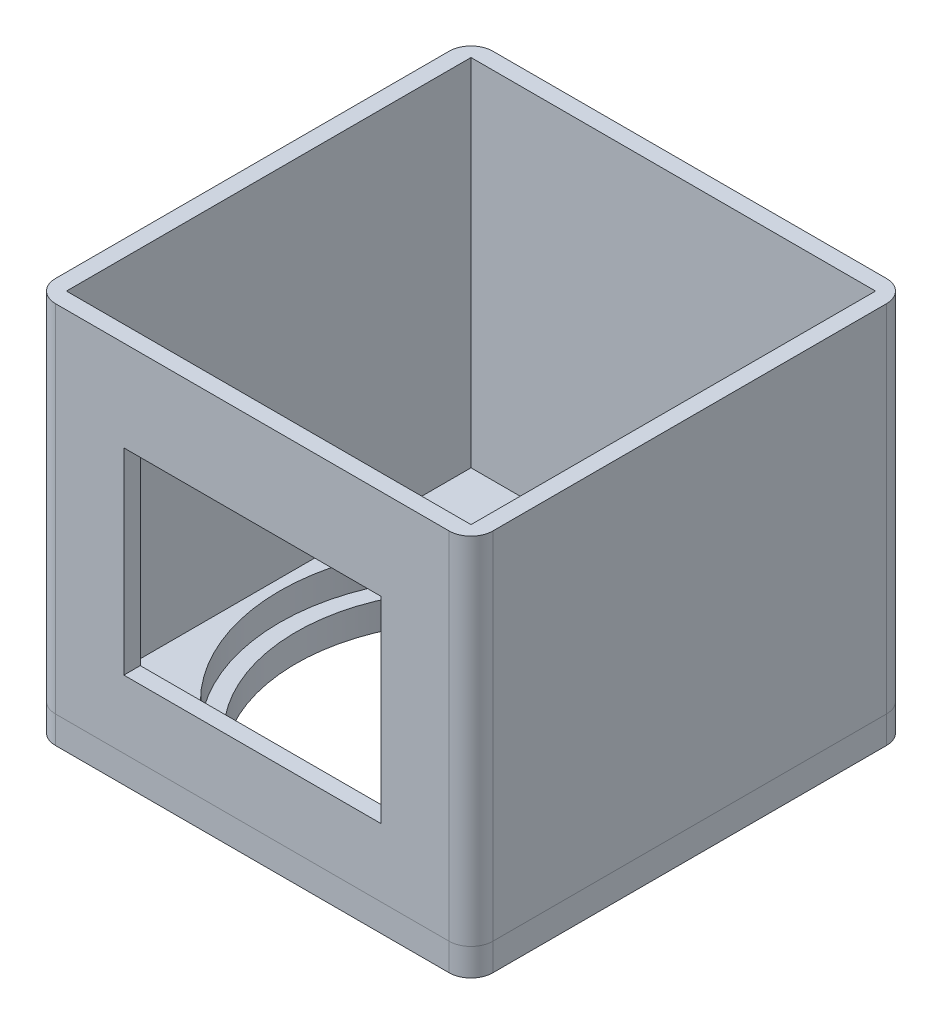
SolidWorks part; units mm, degrees
ref_plane "Front Plane" through (0, 0, 0) normal (0, 0, 1) x (1, 0, 0)
ref_plane "Top Plane" through (0, 0, 0) normal (0, 1, 0) x (1, 0, 0)
ref_plane "Right Plane" through (0, 0, 0) normal (1, 0, 0) x (0, 0, -1)
sketch "Sketch1" plane through (0, 0, 0) normal (0, 1, 0) x (1, 0, 0)
  circle A0 centre (0, 0) radius 35
  circle A1 centre (0, 0) radius 32
  dimension "D1" = 70
  dimension "D2" = 64
extrude "Boss-Extrude1" add sketch "Sketch1" along normal blind 5
sketch "Sketch2" plane through (0, 5, 0) normal (0, 1, 0) x (1, 0, 0)
  line L1 (-40, 40) -> (40, 40)
  line L2 (-40, 40) -> (-40, -40)
  line L3 (-40, -40) -> (40, -40)
  line L4 (40, 40) -> (40, -40)
  line L5 (-40, 40) -> (40, -40) construction
  line L6 (-40, -40) -> (40, 40) construction
  circle A3 centre (0, 0) radius 35
  point P0 (0, 0)
  dimension "D1" = 80
  dimension "D2" = 80
extrude "Boss-Extrude3" add sketch "Sketch2" along normal blind 5
sketch "Sketch9" plane through (0, 10, 0) normal (0, 1, 0) x (1, 0, 0)
  line L1 (-40, 40) -> (40, 40)
  line L2 (-40, 40) -> (-40, -40)
  line L3 (-40, -40) -> (40, -40)
  line L4 (40, 40) -> (40, -40)
  line L5 (-37, 37) -> (37, 37)
  line L6 (-37, 37) -> (-37, -37)
  line L7 (-37, -37) -> (37, -37)
  line L8 (37, 37) -> (37, -37)
  line L9 (-37, 37) -> (37, -37) construction
  line L10 (-37, -37) -> (37, 37) construction
  point P6 (0, 0)
  dimension "D1" = 74
  dimension "D2" = 74
extrude "Boss-Extrude4" add sketch "Sketch9" along normal blind 65
sketch "Sketch11" plane through (0, 0, 40) normal (0, 0, 1) x (1, 0, 0)
  line L0 (0, -5.5) -> (0, 5.5) construction
  line L1 (-23.5, 58.4109) -> (23.5, 58.4109)
  line L2 (-23.5, 58.4109) -> (-23.5, 22.4109)
  line L3 (-23.5, 22.4109) -> (23.5, 22.4109)
  line L4 (23.5, 58.4109) -> (23.5, 22.4109)
  line L5 (-23.5, 58.4109) -> (23.5, 22.4109) construction
  line L6 (-23.5, 22.4109) -> (23.5, 58.4109) construction
  point P0 (0, 40.4109)
  dimension "D1" = 47
  dimension "D2" = 36
extrude "Cut-Extrude2" cut sketch "Sketch11" against normal up to next (3 mm away) contours L2 L3 L4 L1
fillet "Fillet1" radius 4 4 edges at (40, 7.5, -40) (40, 7.5, 40) (-40, 7.5, 40) (-40, 7.5, -40)
fillet "Fillet2" radius 4 4 edges at (40, 42.5, 40) (40, 42.5, -40) (-40, 42.5, 40) (-40, 42.5, -40)
